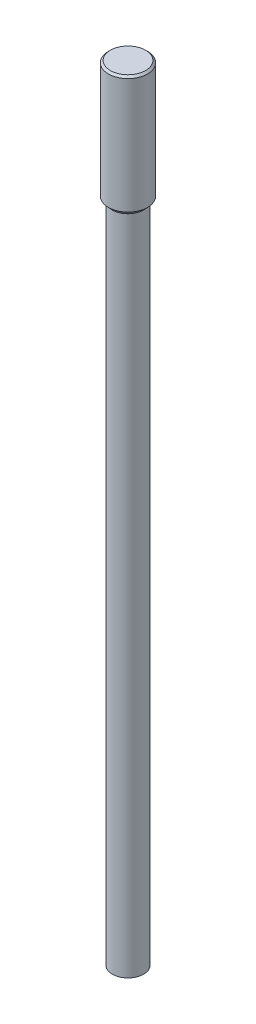
SolidWorks part; units mm, degrees
ref_plane "Płaszczyzna przednia" through (0, 0, 0) normal (0, 0, 1) x (1, 0, 0)
ref_plane "Płaszczyzna górna" through (0, 0, 0) normal (0, 1, 0) x (1, 0, 0)
ref_plane "Płaszczyzna prawa" through (0, 0, 0) normal (1, 0, 0) x (0, 0, -1)
sketch "Szkic1" plane through (0, 0, 0) normal (0, 0, 1) x (1, 0, 0)
  line L0 (0, 109.9178) -> (0, -90.0822) construction
  line L1 (0, 109.9178) -> (-5, 109.9178)
  line L2 (-5, 109.9178) -> (-5, 79.9178)
  line L3 (-5, 79.9178) -> (-4, 78.8368)
  line L4 (-4, 78.8368) -> (-4, -90.0822)
  line L5 (-4, -90.0822) -> (0, -90.0822)
  line L6 (0, 109.9178) -> (0, -90.0822)
  dimension "D1" = 4
  dimension "D2" = 5
  dimension "D3" = 200
  dimension "D4" = 30
revolve "Obrót1" add sketch "Szkic1" angle 360 about L0
chamfer "Sfazowanie1" distance 0.5 angle 45 1 edges at (-5, 109.9178, 0)
